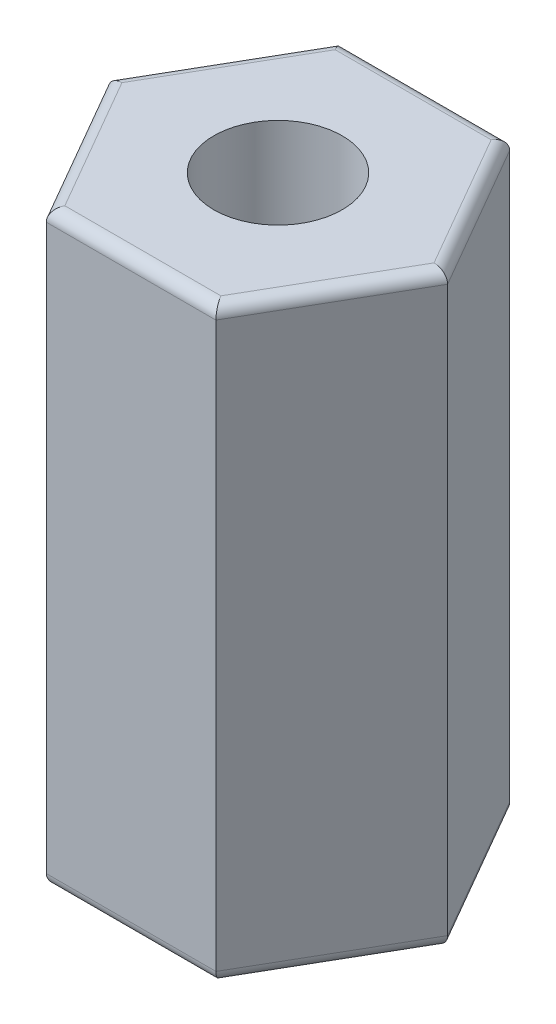
SolidWorks part; units mm, degrees
material "201.0-T43 Molde de fundição com isolamento (SS)"
ref_plane "Plano frontal" through (0, 0, 0) normal (0, 0, 1) x (1, 0, 0)
ref_plane "Plano superior" through (0, 0, 0) normal (0, 1, 0) x (1, 0, 0)
ref_plane "Plano direito" through (0, 0, 0) normal (1, 0, 0) x (0, 0, -1)
sketch "Esboço1" plane through (0, 0, 0) normal (0, 1, 0) x (1, 0, 0)
  line L1 (2.8868, 0) -> (1.4434, 2.5)
  line L2 (1.4434, 2.5) -> (-1.4434, 2.5)
  line L3 (-1.4434, 2.5) -> (-2.8868, 0)
  line L4 (-2.8868, 0) -> (-1.4434, -2.5)
  line L5 (-1.4434, -2.5) -> (1.4434, -2.5)
  line L6 (1.4434, -2.5) -> (2.8868, 0)
  circle A0 centre (0, 0) radius 2.5 construction
  dimension "D1" = 5
extrude "Ressalto-extrusão1" add sketch "Esboço1" along normal blind 10
fillet "Filete1" radius 0.2 12 edges at (0, 10, -2.5) (-2.1651, 10, -1.25) (-2.1651, 10, 1.25) (0, 10, 2.5) (2.1651, 10, 1.25) (2.1651, 10, -1.25) (0, 0, 2.5) (-2.1651, 0, 1.25) (-2.1651, 0, -1.25) (0, 0, -2.5) (2.1651, 0, -1.25) (2.1651, 0, 1.25)
sketch "Esboço2" plane through (0, 0, 0) normal (0, -1, 0) x (1, 0, 0)
  circle A0 centre (0, 0) radius 1.0922
  dimension "D1" = 2.1844
sketch "Esboço3" plane through (0, 10, 0) normal (0, 1, 0) x (1, 0, 0)
  circle A0 centre (0, 0) radius 1.0922
extrude "Corte-extrusão1" cut sketch "Esboço3" against normal blind 5
extrude "Corte-extrusão2" cut sketch "Esboço2" against normal blind 5 contours A0
